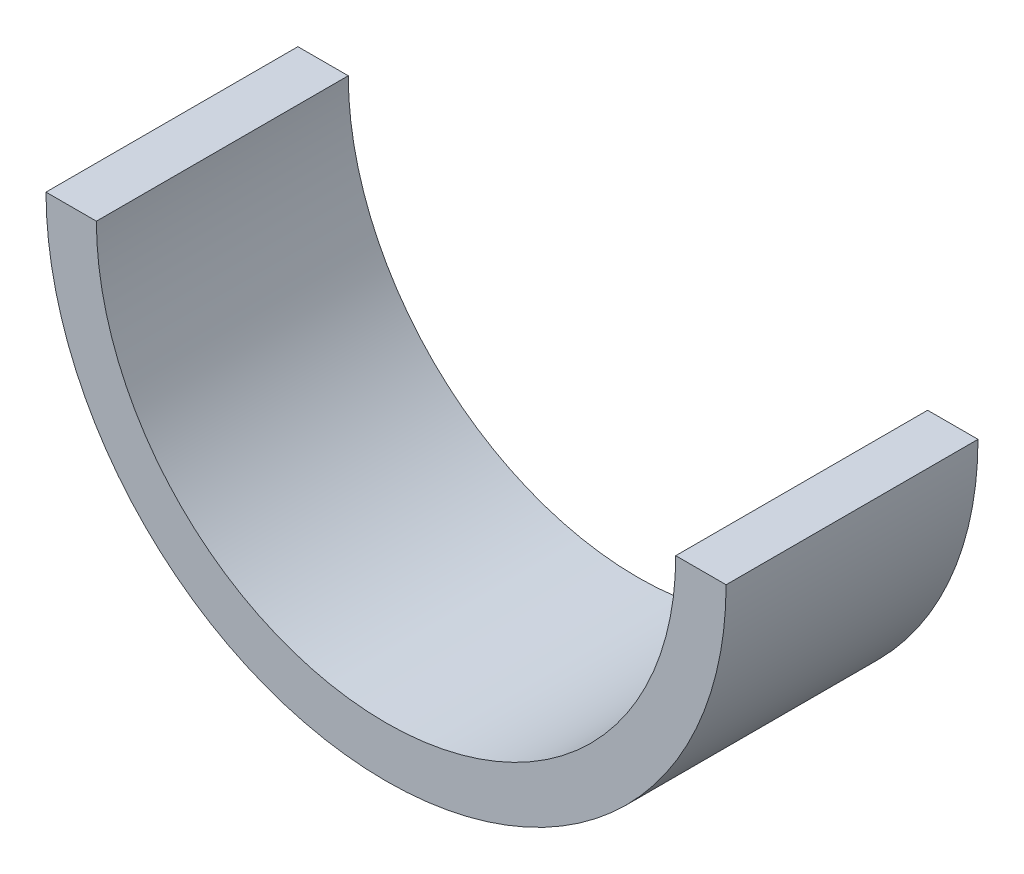
SolidWorks part; units mm, degrees
ref_plane "Front Plane" through (0, 0, 0) normal (0, 0, 1) x (1, 0, 0)
ref_plane "Top Plane" through (0, 0, 0) normal (0, 1, 0) x (1, 0, 0)
ref_plane "Right Plane" through (0, 0, 0) normal (1, 0, 0) x (0, 0, -1)
sketch "Sketch1" plane through (0, 0, 0) normal (0, 0, 1) x (1, 0, 0)
  line L0 (54, 27) -> (50, 27)
  line L1 (4, 27) -> (0, 27)
  arc A0 (0, 27) -> (54, 27) centre (27, 27) ccw
  arc A1 (50, 27) -> (4, 27) centre (27, 27) cw
  dimension "D1" = 27
  dimension "D2" = 23
extrude "Profile" add sketch "Sketch1" along normal blind 20
equation "\"Profile_Depth\"= 20mm"
equation "\"D1@Profile\" = \"Profile_Depth\""
equation "\"Profile_Sketch_1\"= 27mm"
equation "\"D1@Sketch1\" = \"Profile_Sketch_1\""
equation "\"Profile_Sketch_2\"= 23mm"
equation "\"D2@Sketch1\" = \"Profile_Sketch_2\""
equation "\"EnvelopeWidth\"= 54mm"
equation "\"EnvelopeHeight\"= 54mm"
